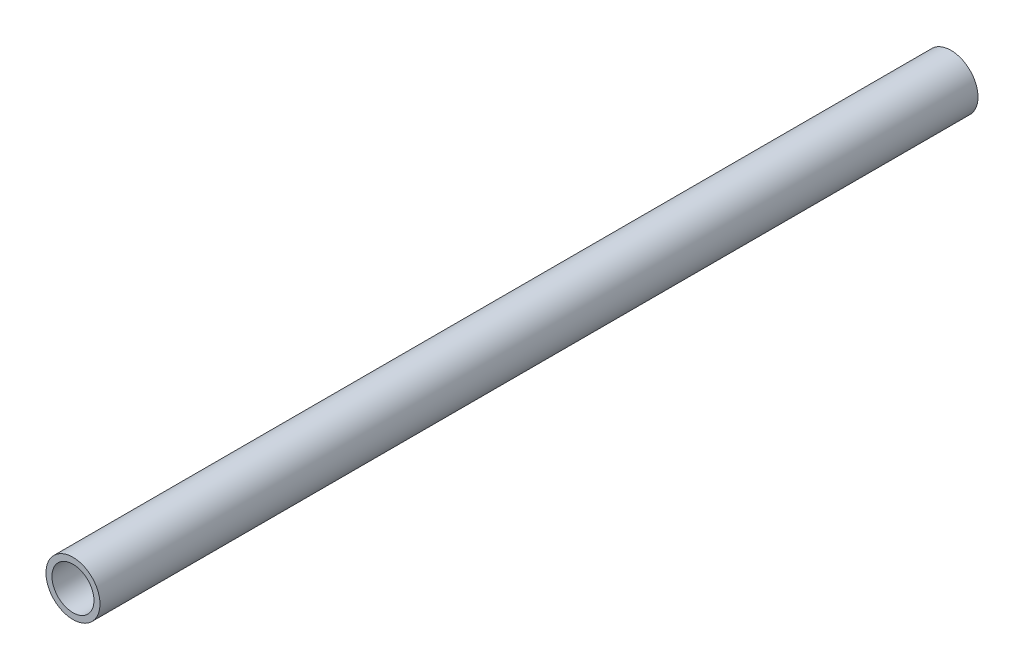
SolidWorks part; units mm, degrees
ref_plane "Front Plane" through (0, 0, 0) normal (0, 0, 1) x (1, 0, 0)
ref_plane "Top Plane" through (0, 0, 0) normal (0, 1, 0) x (1, 0, 0)
ref_plane "Right Plane" through (0, 0, 0) normal (1, 0, 0) x (0, 0, -1)
sketch "Sketch1" plane through (0, 0, 0) normal (0, 0, 1) x (1, 0, 0)
  circle A0 centre (0, 0) radius 7
  circle A1 centre (0, 0) radius 9
  dimension "D1" = 14
  dimension "D2" = 18
extrude "Boss-Extrude1" add sketch "Sketch1" along normal blind 292.66
